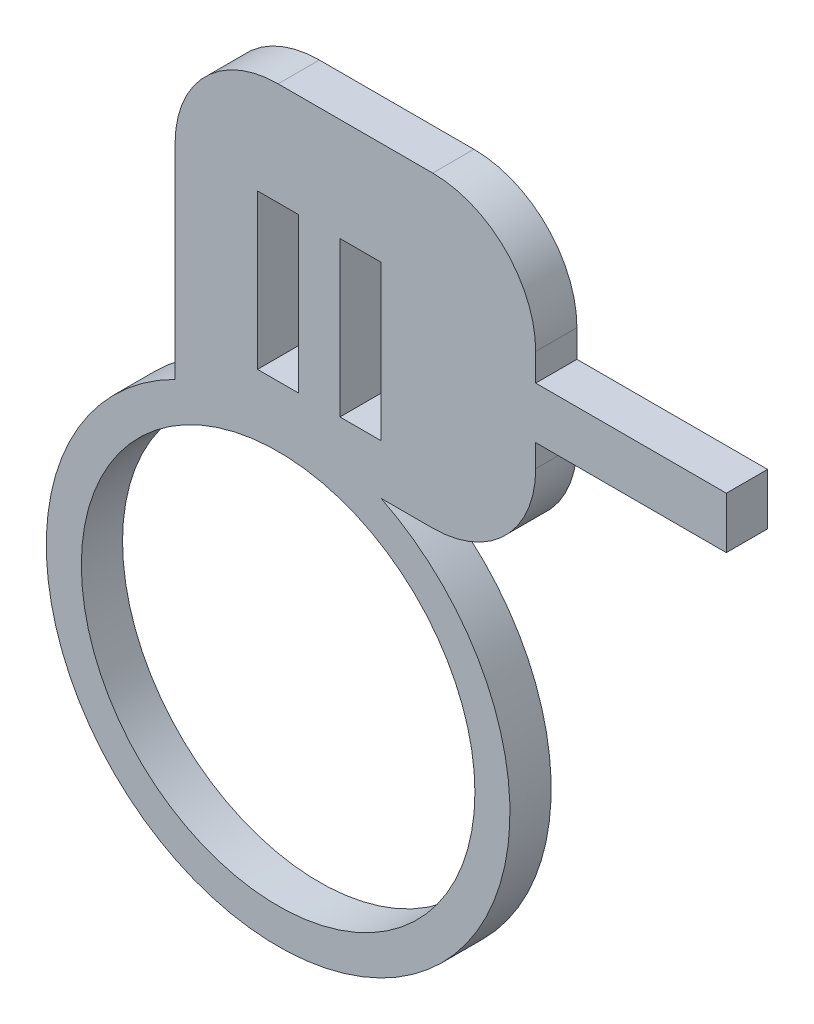
SolidWorks part; units mm, degrees
ref_plane "Front Plane" through (0, 0, 0) normal (0, 0, 1) x (1, 0, 0)
ref_plane "Top Plane" through (0, 0, 0) normal (0, 1, 0) x (1, 0, 0)
ref_plane "Right Plane" through (0, 0, 0) normal (1, 0, 0) x (0, 0, -1)
sketch "Sketch1" plane through (0, 0, 0) normal (0, 0, 1) x (1, 0, 0)
  circle A0 centre (0, 0) radius 28.575
  dimension "D2" = 57.15
extrude "Boss-Extrude1" add sketch "Sketch1" along normal blind 5.08
sketch "Sketch2" plane through (0, 0, 0) normal (0, 1, 0) x (1, 0, 0)
  line L2 (-12.7, 0) -> (12.7, 0)
  line L3 (-12.7, 0) -> (-12.7, -5.08)
  line L4 (-12.7, -5.08) -> (12.7, -5.08)
  line L5 (12.7, 0) -> (12.7, -5.08)
  line L6 (-12.7, 0) -> (12.7, -5.08) construction
  line L7 (-12.7, -5.08) -> (12.7, 0) construction
  point P4 (0, -2.54)
  dimension "D1" = 5.08
  dimension "D2" = 25.4
extrude "Boss-Extrude2" add sketch "Sketch2" along normal blind 63.5
sketch "Sketch3" plane through (0, 0, 0) normal (0, 0, -1) x (-1, 0, 0)
  circle A0 centre (0, 0) radius 24.257
  dimension "D1" = 48.514
extrude "Cut-Extrude1" cut sketch "Sketch3" against normal blind 50.8
sketch "Sketch4" plane through (0, 0, 0) normal (0, 0, -1) x (-1, 0, 0)
  line L0 (-2.54, 50.8) -> (-2.54, 63.5) construction
  line L1 (12.7, 63.5) -> (-12.7, 63.5) construction
  line L2 (12.7, 63.5) -> (12.7, 25.5977) construction
  line L3 (12.7, 25.5977) -> (-12.7, 25.5977) construction
  line L4 (-12.7, 63.5) -> (-12.7, 25.5977) construction
  line L5 (2.54, 50.8) -> (-2.54, 50.8)
  line L6 (2.54, 50.8) -> (2.54, 31.75)
  line L7 (2.54, 31.75) -> (-2.54, 31.75)
  line L8 (-2.54, 50.8) -> (-2.54, 31.75)
  line L9 (2.54, 50.8) -> (-2.54, 31.75) construction
  line L10 (2.54, 31.75) -> (-2.54, 50.8) construction
  line L11 (-2.54, 50.8) -> (-12.7, 50.8) construction
  line L12 (2.54, 50.8) -> (12.7, 50.8) construction
  point P6 (0, 41.275)
  dimension "D1" = 5.08
  dimension "D2" = 19.05
  dimension "D3" = 12.7
extrude "Cut-Extrude2" cut sketch "Sketch4" against normal blind 50.8
sketch "Sketch6" plane through (12.7, 0, 0) normal (1, 0, 0) x (0, 0, -1)
  line L1 (0, 25.5977) -> (-5.08, 25.5977)
  line L2 (0, 25.5977) -> (0, 63.5)
  line L3 (0, 63.5) -> (-5.08, 63.5)
  line L4 (-5.08, 25.5977) -> (-5.08, 63.5)
extrude "Boss-Extrude4" add sketch "Sketch6" along normal blind 19.05
sketch "Sketch7" plane through (0, 0, 5.08) normal (0, 0, 1) x (1, 0, 0)
  line L0 (2.54, 31.75) -> (7.62, 31.75) construction
  line L1 (2.54, 50.8) -> (7.62, 50.8) construction
  line L3 (7.62, 31.75) -> (12.7, 31.75)
  line L4 (7.62, 31.75) -> (7.62, 50.8)
  line L5 (7.62, 50.8) -> (12.7, 50.8)
  line L6 (12.7, 31.75) -> (12.7, 50.8)
  dimension "D1" = 5.08
  dimension "D2" = 5.08
extrude "Cut-Extrude3" cut sketch "Sketch7" against normal blind 25.4
fillet "Fillet1" radius 12.7 3 edges at (31.75, 25.5977, 2.54) (-12.7, 63.5, 2.54) (31.75, 63.5, 2.54)
sketch "Sketch8" plane through (31.75, 0, 0) normal (1, 0, 0) x (0, 0, -1)
  line L0 (0, 38.2977) -> (0, 50.8) construction
  line L1 (0, 41.0769) -> (-5.08, 41.0769)
  line L2 (0, 41.0769) -> (0, 47.4269)
  line L3 (0, 47.4269) -> (-5.08, 47.4269)
  line L4 (-5.08, 41.0769) -> (-5.08, 47.4269)
  line L5 (-5.08, 50.8) -> (-5.08, 38.2977) construction
  dimension "D1" = 6.35
extrude "Boss-Extrude5" add sketch "Sketch8" along normal blind 23.495
equation "\"Foamcore\" = .1in"
equation "\"MDF\" = .2in"
equation "\"Gmaterial\"= \"MDF\""
equation "\"PVC-ID\" = \"1.590in\""
equation "\"PVC-OD\" = \"1.900in\""
equation "\"PVC-Sleeve-Width\" = \".51in\""
equation "\"D1@Boss-Extrude1\"=\"Gmaterial\""
equation "\"D2@Sketch4\"=.75"
equation "\"D1@Sketch4\"=\"Gmaterial\""
equation "\"D2@Sketch7\"=\"Gmaterial\""
equation "\"gmater\"=0.3"
equation "\"D1@Sketch7\" = \"Gmaterial\""
equation "\"D1@Sketch2\"=\"Gmaterial\""
